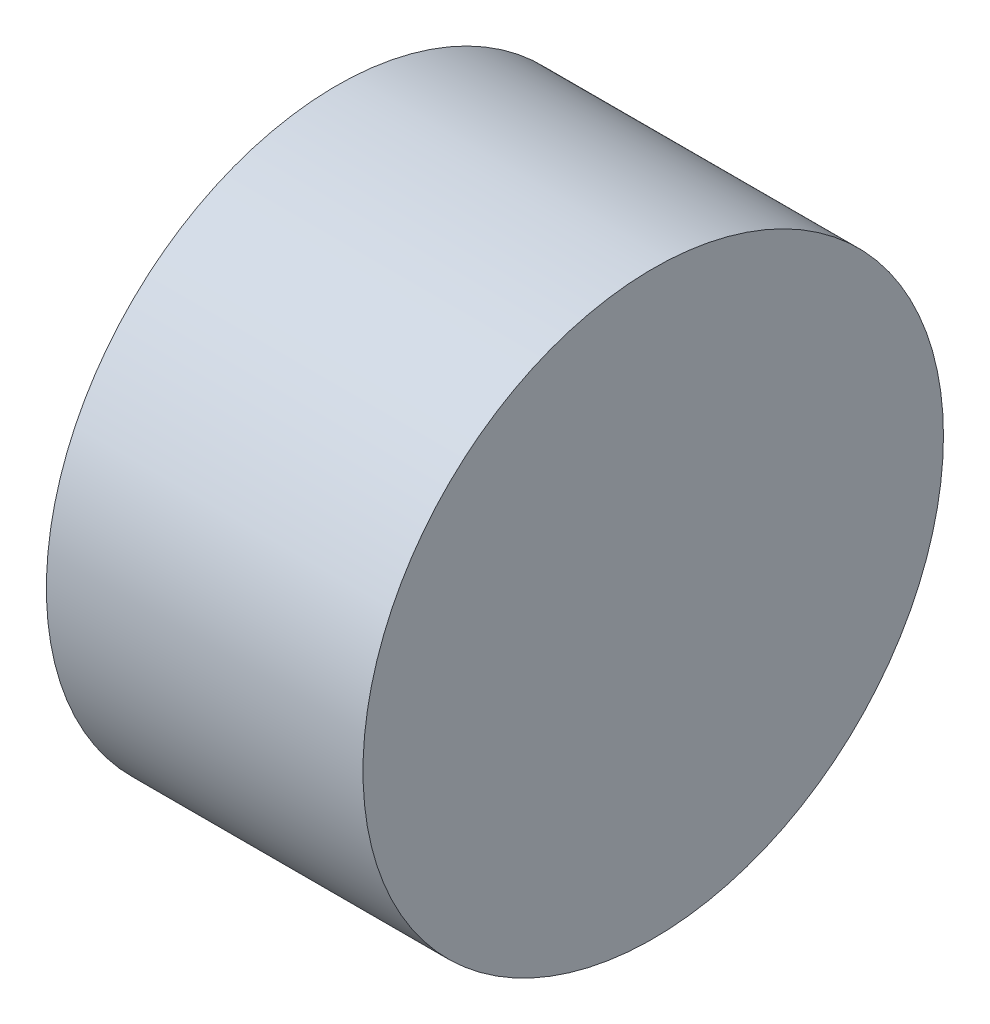
SolidWorks part; units mm, degrees
ref_plane "Front Plane" through (0, 0, 0) normal (0, 0, 1) x (1, 0, 0)
ref_plane "Top Plane" through (0, 0, 0) normal (0, 1, 0) x (1, 0, 0)
ref_plane "Right Plane" through (0, 0, 0) normal (1, 0, 0) x (0, 0, -1)
sketch "Sketch1" plane through (0, 0, 0) normal (1, 0, 0) x (0, 0, -1)
  circle A0 centre (0, 0) radius 27.5
  dimension "D1" = 55
extrude "Boss-Extrude1" add sketch "Sketch1" along normal blind 30
